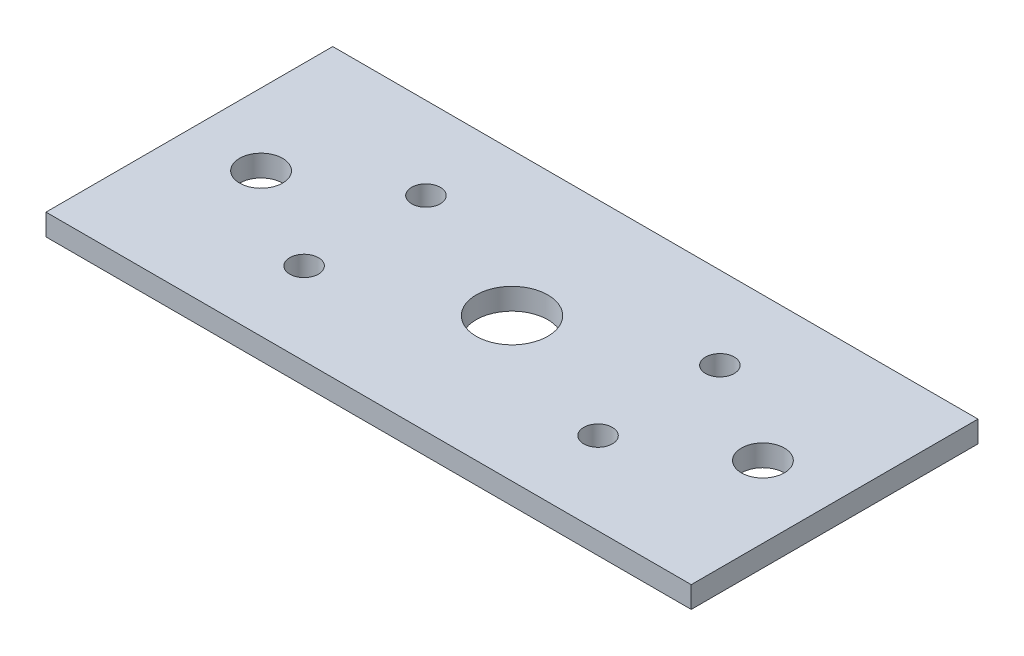
SolidWorks part; units mm, degrees
ref_plane "前视基准面" through (0, 0, 0) normal (0, 0, 1) x (1, 0, 0)
ref_plane "上视基准面" through (0, 0, 0) normal (0, 1, 0) x (1, 0, 0)
ref_plane "右视基准面" through (0, 0, 0) normal (1, 0, 0) x (0, 0, -1)
sketch "草图1" plane through (0, 0, 0) normal (0, 1, 0) x (1, 0, 0)
  line L0 (-45, -20) -> (45, -20)
  line L1 (-45, -20) -> (-45, 20)
  line L2 (45, -20) -> (45, 20)
  line L3 (-45, 20) -> (45, 20)
  line L4 (-45, -20) -> (45, 20) construction
  line L5 (45, -20) -> (-45, 20) construction
  line L6 (-45, 0) -> (-35, 0)
  line L7 (45, 0) -> (35, 0)
  line L8 (-20.5, -8.5) -> (20.5, -8.5)
  line L9 (-20.5, -8.5) -> (-20.5, 8.5)
  line L10 (20.5, -8.5) -> (20.5, 8.5)
  line L11 (-20.5, 8.5) -> (20.5, 8.5)
  line L12 (-20.5, -8.5) -> (20.5, 8.5) construction
  line L13 (20.5, -8.5) -> (-20.5, 8.5) construction
  circle A0 centre (0, 0) radius 5
  circle A1 centre (-35, 0) radius 3
  circle A2 centre (35, 0) radius 3
  circle A3 centre (-20.5, 8.5) radius 2
  circle A4 centre (20.5, 8.5) radius 2
  circle A5 centre (20.5, -8.5) radius 2
  circle A6 centre (-20.5, -8.5) radius 2
  point P1 (0, 0)
  dimension "D3" = 10
  dimension "D7" = 4
  dimension "D8" = 4
  dimension "D9" = 4
  dimension "D10" = 4
  dimension "D11" = 10
  dimension "D1" = 40
  dimension "D2" = 90
  dimension "D4" = 10
  dimension "D5" = 41
  dimension "D6" = 17
extrude "凸台-拉伸1" add sketch "草图1" along normal blind 3
